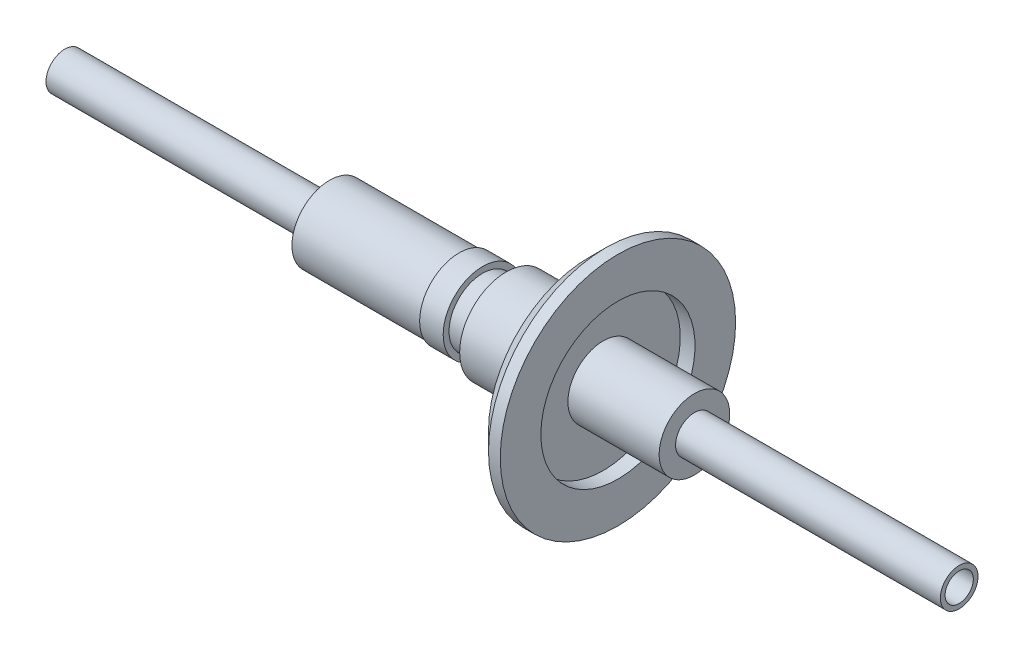
SolidWorks part; units mm, degrees
ref_plane "Front Plane" through (0, 0, 0) normal (0, 0, 1) x (1, 0, 0)
ref_plane "Top Plane" through (0, 0, 0) normal (0, 1, 0) x (1, 0, 0)
ref_plane "Right Plane" through (0, 0, 0) normal (1, 0, 0) x (0, 0, -1)
sketch "Axial profile (mm)" plane through (0, 0, 0) normal (0, 0, 1) x (1, 0, 0)
  line L0 (-110, 0) -> (75, 0) construction
  line L1 (-94, 2.4) -> (58, 2.4)
  line L2 (58, 2.4) -> (58, 3.2)
  line L3 (58, 3.2) -> (13, 3.2)
  line L4 (13, 3.2) -> (13, 6)
  line L5 (13, 6) -> (-2.5, 6)
  line L6 (-2.5, 6) -> (-2.5, 13.1)
  line L7 (-2.5, 13.1) -> (0, 13.1)
  line L8 (0, 13.1) -> (0, 20)
  line L9 (0, 20) -> (-2, 20)
  line L10 (-2, 20) -> (-5, 17)
  line L11 (-5, 17) -> (-5, 7.9)
  line L12 (-5, 7.9) -> (-19, 7.9)
  line L13 (-19, 7.9) -> (-19, 5.7)
  line L14 (-19, 5.7) -> (-23, 5.7)
  line L15 (-23, 5.7) -> (-23, 6.7)
  line L16 (-23, 6.7) -> (-27, 6.7)
  line L17 (-27, 6.7) -> (-27, 6.4)
  line L18 (-27, 6.4) -> (-49, 6.4)
  line L19 (-49, 6.4) -> (-49, 3.2)
  line L20 (-49, 3.2) -> (-94, 3.2)
  line L21 (-94, 3.2) -> (-94, 2.4)
revolve "Full revolution" add sketch "Axial profile (mm)" angle 360 about L0
